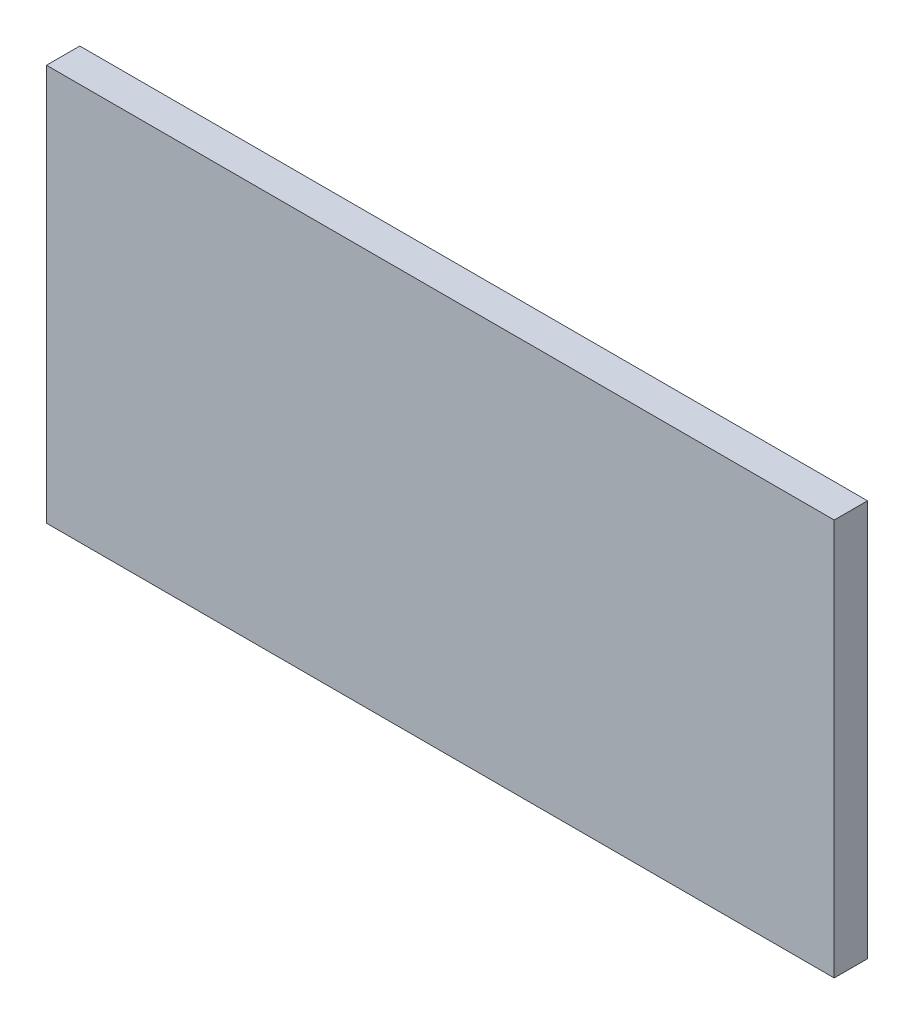
SolidWorks part; units mm, degrees
ref_plane "Plan de face" through (0, 0, 0) normal (0, 0, 1) x (1, 0, 0)
ref_plane "Plan de dessus" through (0, 0, 0) normal (0, 1, 0) x (1, 0, 0)
ref_plane "Plan de droite" through (0, 0, 0) normal (1, 0, 0) x (0, 0, -1)
sketch "Esquisse1" plane through (0, 0, 0) normal (0, 0, 1) x (1, 0, 0)
  line L1 (0, 0) -> (-142, 0)
  line L2 (0, 0) -> (0, 71.5)
  line L3 (0, 71.5) -> (-142, 71.5)
  line L4 (-142, 0) -> (-142, 71.5)
  dimension "D1" = 142
  dimension "D2" = 71.5
extrude "Boss.-Extru.1" add sketch "Esquisse1" along normal blind 6
